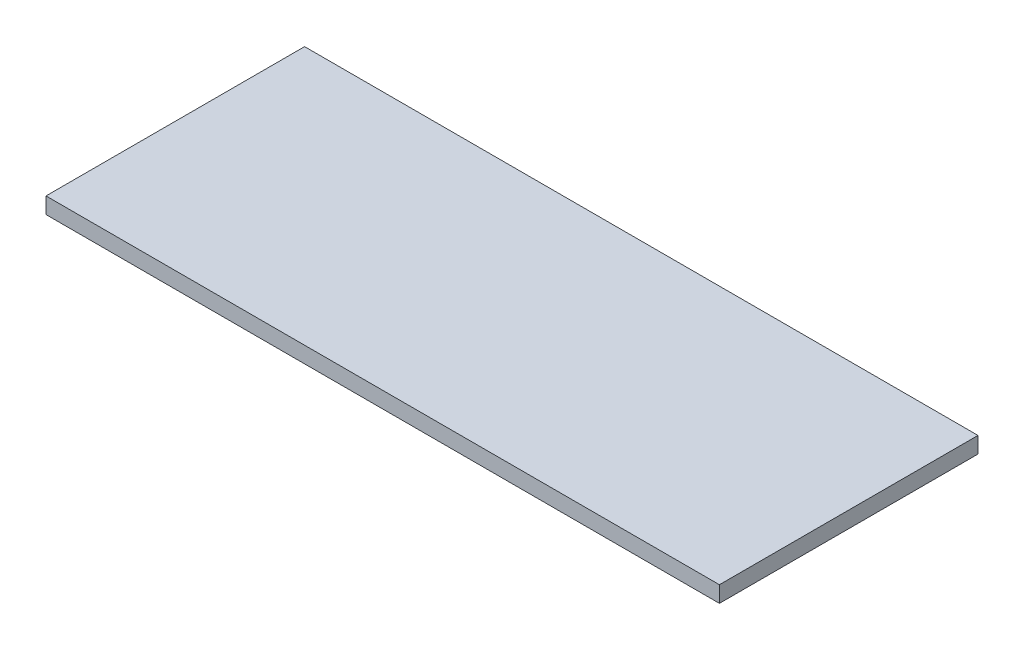
SolidWorks part; units mm, degrees
ref_plane "Front Plane" through (0, 0, 0) normal (0, 0, 1) x (1, 0, 0)
ref_plane "Top Plane" through (0, 0, 0) normal (0, 1, 0) x (1, 0, 0)
ref_plane "Right Plane" through (0, 0, 0) normal (1, 0, 0) x (0, 0, -1)
sketch "Sketch1" plane through (0, 0, 0) normal (0, 1, 0) x (1, 0, 0)
  line L1 (-62.5, -24) -> (62.5, -24)
  line L2 (-62.5, -24) -> (-62.5, 24)
  line L3 (-62.5, 24) -> (62.5, 24)
  line L4 (62.5, -24) -> (62.5, 24)
  line L5 (-62.5, -24) -> (62.5, 24) construction
  line L6 (-62.5, 24) -> (62.5, -24) construction
  point P0 (0, 0)
  dimension "D1" = 125
  dimension "D2" = 48
extrude "Boss-Extrude1" add sketch "Sketch1" along normal blind 3
